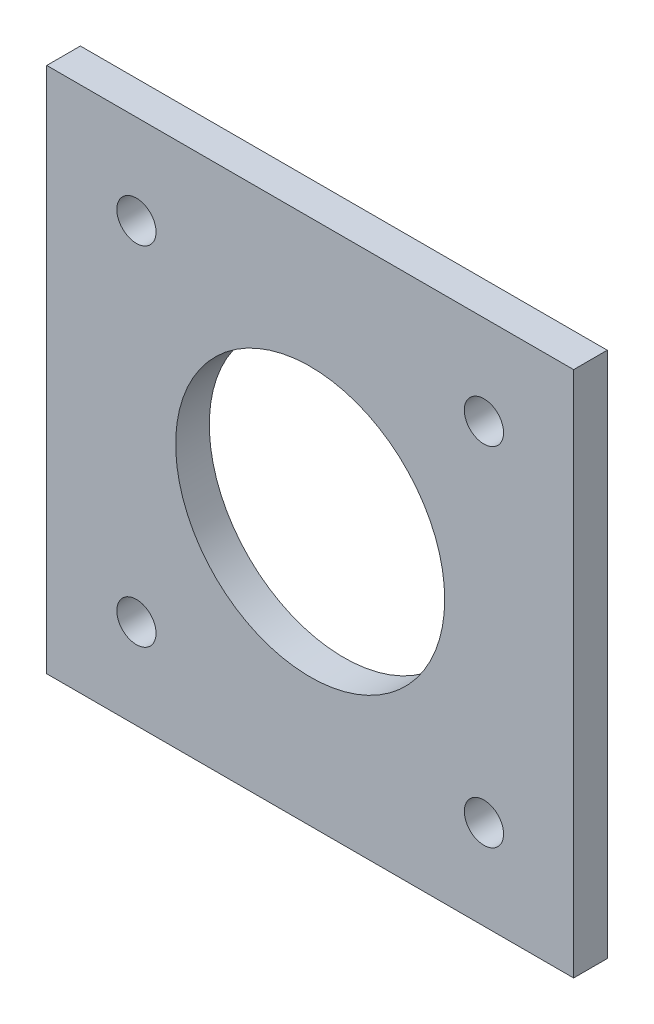
SolidWorks part; units mm, degrees
ref_plane "Front Plane" through (0, 0, 0) normal (0, 0, 1) x (1, 0, 0)
ref_plane "Top Plane" through (0, 0, 0) normal (0, 1, 0) x (1, 0, 0)
ref_plane "Right Plane" through (0, 0, 0) normal (1, 0, 0) x (0, 0, -1)
sketch "Sketch1" plane through (0, 0, 0) normal (0, 0, 1) x (1, 0, 0)
  line L0 (0, 0) -> (-15.5, 15.5) construction
  line L1 (-23.5, -23.5) -> (23.5, -23.5)
  line L2 (-23.5, -23.5) -> (-23.5, 23.5)
  line L3 (-23.5, 23.5) -> (23.5, 23.5)
  line L4 (23.5, -23.5) -> (23.5, 23.5)
  line L5 (-23.5, -23.5) -> (23.5, 23.5) construction
  line L6 (-23.5, 23.5) -> (23.5, -23.5) construction
  line L7 (0, 0) -> (15.5, 15.5) construction
  circle A0 centre (-15.5, 15.5) radius 1.75
  circle A1 centre (15.5, 15.5) radius 1.75
  circle A2 centre (15.5, -15.5) radius 1.75
  circle A3 centre (-15.5, -15.5) radius 1.75
  circle A4 centre (0, 0) radius 12
  point P0 (0, 0)
  dimension "D3" = 3.5
  dimension "D6" = 31
  dimension "D7" = 31
  dimension "D8" = 15.5
  dimension "D1" = 47
  dimension "D2" = 47
  dimension "D5" = 90
  dimension "D4" = 4
extrude "Boss-Extrude1" add sketch "Sketch1" along normal blind 3
